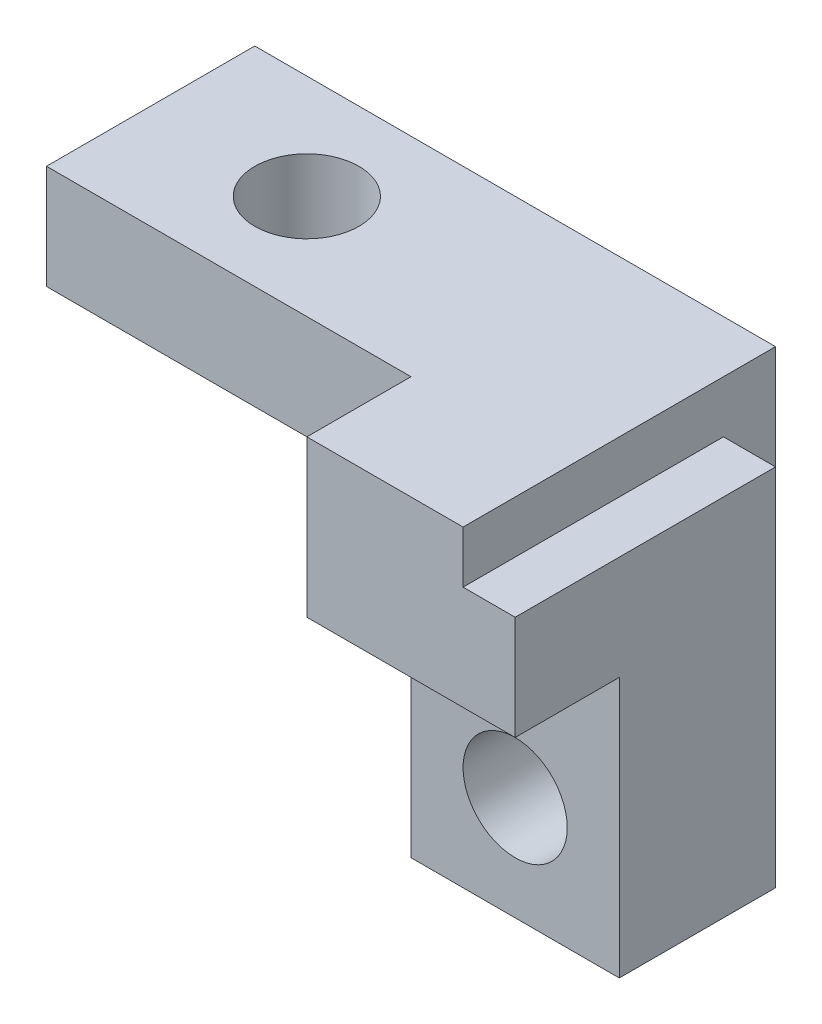
SolidWorks part; units mm, degrees
ref_plane "Front Plane" through (0, 0, 0) normal (0, 0, 1) x (1, 0, 0)
ref_plane "Top Plane" through (0, 0, 0) normal (0, 1, 0) x (1, 0, 0)
ref_plane "Right Plane" through (0, 0, 0) normal (1, 0, 0) x (0, 0, -1)
sketch "Front" plane through (0, 0, 0) normal (0, 0, 1) x (1, 0, 0)
  line L0 (101.6, 104.775) -> (101.6, 130.175)
  line L1 (101.6, 130.175) -> (127, 130.175)
  line L2 (127, 130.175) -> (152.4, 130.175)
  line L3 (152.4, 130.175) -> (228.6, 130.175)
  line L4 (228.6, 130.175) -> (228.6, 117.475)
  line L5 (228.6, 117.475) -> (228.6, 104.775) construction
  line L6 (228.6, 104.775) -> (190.5, 104.775) construction
  line L7 (190.5, 104.775) -> (139.7, 104.775)
  line L8 (139.7, 104.775) -> (127, 104.775)
  line L9 (127, 104.775) -> (101.6, 104.775)
  line L10 (127, 104.775) -> (127, 130.175) construction
  line L11 (152.4, 104.775) -> (152.4, 130.175) construction
  line L12 (190.5, 104.775) -> (190.5, 117.475)
  line L13 (190.5, 117.475) -> (241.3, 117.475)
  line L14 (241.3, 117.475) -> (241.3, 92.075)
  line L15 (241.3, 92.075) -> (190.5, 92.075)
  line L16 (190.5, 92.075) -> (190.5, 104.775)
  line L17 (190.5, 92.075) -> (190.5, 28.575)
  line L18 (190.5, 28.575) -> (241.3, 28.575)
  line L19 (241.3, 28.575) -> (241.3, 92.075)
  line L20 (139.7, 98.425) -> (139.7, 136.525) construction
  line L21 (196.85, 53.975) -> (234.95, 53.975) construction
  line L22 (215.9, 34.925) -> (215.9, 73.025) construction
  circle A0 centre (215.9, 53.975) radius 12.7
sketch "Top" plane through (0, 130.175, 0) normal (0, 1, 0) x (-1, 0, 0)
  line L0 (-241.3, 0) -> (-190.5, 0)
  line L1 (-190.5, 0) -> (-190.5, -25.4)
  line L2 (-190.5, -25.4) -> (-101.6, -25.4)
  line L3 (-101.6, -25.4) -> (-101.6, -76.2)
  line L4 (-101.6, -76.2) -> (-228.6, -76.2)
  line L5 (-228.6, -76.2) -> (-228.6, -63.5)
  line L6 (-228.6, -63.5) -> (-241.3, -63.5)
  line L7 (-241.3, -63.5) -> (-241.3, 0)
  line L8 (-228.6, -63.5) -> (-190.5, -63.5) construction
  line L9 (-190.5, -63.5) -> (-190.5, -25.4) construction
  line L10 (-190.5, -25.4) -> (-228.6, -25.4)
  line L11 (-228.6, -25.4) -> (-228.6, -63.5)
  line L12 (-228.6, -25.4) -> (-241.3, -25.4) construction
  line L13 (-203.2, -25.4) -> (-203.2, -63.5) construction
  line L14 (-215.9, -19.05) -> (-215.9, -69.85) construction
  line L15 (-120.65, -50.8) -> (-158.75, -50.8) construction
  line L16 (-139.7, -31.75) -> (-139.7, -69.85) construction
  circle A0 centre (-139.7, -50.8) radius 12.7
sketch "Right" plane through (241.3, 0, 0) normal (1, 0, 0) x (0, 0, -1)
  line L0 (76.2, 130.175) -> (25.4, 130.175)
  line L1 (63.5, 117.475) -> (0, 117.475)
  line L2 (63.5, 117.475) -> (63.5, 28.575)
  line L3 (76.2, 130.175) -> (76.2, 104.775)
  line L4 (25.4, 130.175) -> (25.4, 117.475)
  line L5 (25.4, 117.475) -> (25.4, 104.775) construction
  line L6 (25.4, 104.775) -> (63.5, 104.775) construction
  line L7 (63.5, 104.775) -> (76.2, 104.775)
  line L8 (0, 117.475) -> (0, 92.075)
  line L9 (0, 92.075) -> (25.4, 92.075)
  line L10 (25.4, 92.075) -> (25.4, 28.575)
  line L11 (25.4, 28.575) -> (63.5, 28.575)
  line L12 (25.4, 66.675) -> (63.5, 66.675) construction
  line L13 (25.4, 41.275) -> (63.5, 41.275) construction
  line L14 (19.05, 53.975) -> (69.85, 53.975) construction
  line L15 (38.1, 130.175) -> (38.1, 104.775) construction
  line L16 (63.5, 130.175) -> (63.5, 117.475) construction
  line L17 (50.8, 136.525) -> (50.8, 98.425) construction
  point P23 (0, 0)
  point P24 (0, 0)
  point P25 (0, 0)
sketch "Sketch5" plane through (0, 130.175, 0) normal (0, 1, 0) x (-1, 0, 0)
  line L0 (-241.3, 0) -> (-190.5, 0)
  line L1 (-190.5, 0) -> (-190.5, -25.4)
  line L2 (-190.5, -25.4) -> (-101.6, -25.4)
  line L3 (-101.6, -25.4) -> (-101.6, -76.2)
  line L4 (-101.6, -76.2) -> (-228.6, -76.2)
  line L5 (-228.6, -76.2) -> (-228.6, -63.5)
  line L6 (-228.6, -63.5) -> (-241.3, -63.5)
  line L7 (-241.3, -63.5) -> (-241.3, 0)
extrude "Boss-Extrude1" add sketch "Sketch5" against normal up to vertex (101.6 mm away) from vertex at 0 up to point (241.3, 28.575, -63.5) starting at point (241.3, 130.175, -76.2)
sketch "Sketch6" plane through (0, 130.175, 0) normal (0, 1, 0) x (-1, 0, 0)
  circle A0 centre (-139.7, -50.8) radius 12.7
extrude "Cut-Extrude1" cut sketch "Sketch6" against normal through all
sketch "Sketch8" plane through (0, 0, 0) normal (0, 0, 1) x (1, 0, 0)
  line L0 (190.5, 104.775) -> (139.7, 104.775)
  line L1 (139.7, 104.775) -> (127, 104.775)
  line L2 (127, 104.775) -> (101.6, 104.775)
  line L3 (190.5, 92.075) -> (190.5, 104.775)
  line L4 (190.5, 92.075) -> (190.5, 28.575)
  line L5 (101.6, 104.775) -> (101.6, 28.575)
  line L6 (101.6, 28.575) -> (190.5, 28.575)
extrude "Cut-Extrude5" cut sketch "Sketch8" against normal through all
sketch "Sketch10" plane through (0, 0, 0) normal (0, 0, 1) x (1, 0, 0)
  line L0 (228.6, 130.175) -> (228.6, 117.475)
  line L1 (190.5, 117.475) -> (241.3, 117.475)
  line L2 (228.6, 130.175) -> (241.3, 130.175)
  line L3 (241.3, 130.175) -> (241.3, 117.475)
extrude "Cut-Extrude6" cut sketch "Sketch10" against normal through all contours L3 L2 L0 L1
sketch "Sketch11" plane through (241.3, 0, 0) normal (1, 0, 0) x (0, 0, -1)
  line L0 (0, 92.075) -> (25.4, 92.075)
  line L1 (25.4, 92.075) -> (25.4, 28.575)
  line L2 (0, 92.075) -> (0, 28.575)
  line L3 (0, 28.575) -> (25.4, 28.575)
extrude "Cut-Extrude7" cut sketch "Sketch11" against normal through all
sketch "Sketch12" plane through (0, 0, 0) normal (0, 0, 1) x (1, 0, 0)
  circle A0 centre (215.9, 53.975) radius 12.7
extrude "Cut-Extrude10" cut sketch "Sketch12" against normal blind 35.56 from vertex at -25.4 starting at point (241.3, 28.575, -25.4)
sketch "Sketch13" plane through (241.3, 0, 0) normal (1, 0, 0) x (0, 0, -1)
  line L0 (63.5, 117.475) -> (63.5, 28.575)
  line L1 (63.5, 104.775) -> (76.2, 104.775)
